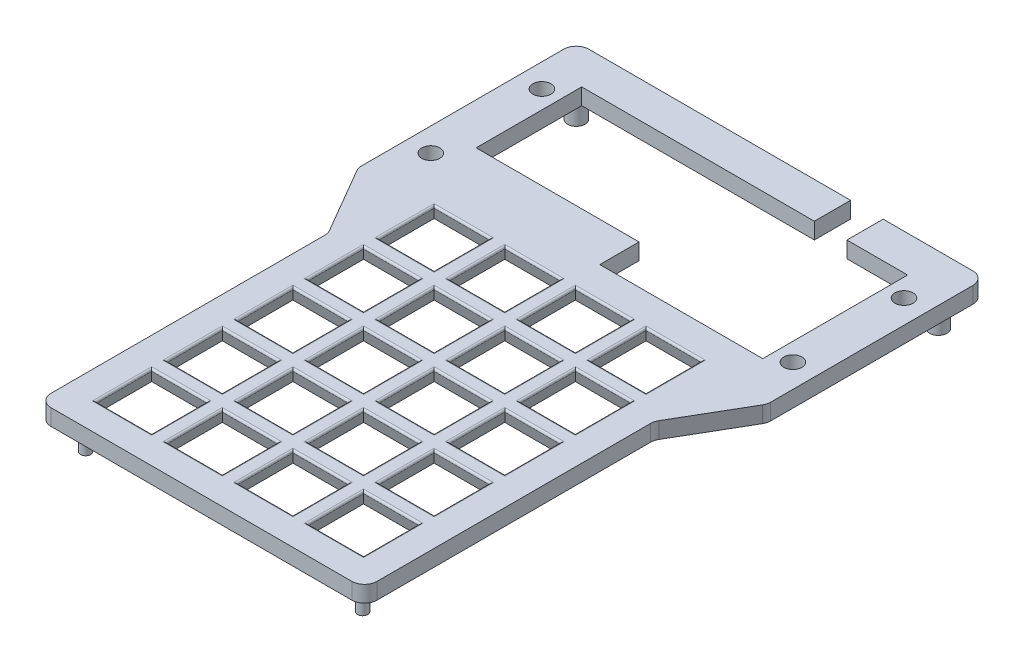
SolidWorks part; units mm, degrees
ref_plane "Front Plane" through (0, 0, 0) normal (0, 0, 1) x (1, 0, 0)
ref_plane "Top Plane" through (0, 0, 0) normal (0, 1, 0) x (1, 0, 0)
ref_plane "Right Plane" through (0, 0, 0) normal (1, 0, 0) x (0, 0, -1)
sketch "Sketch1" plane through (0, 0, 0) normal (0, 1, 0) x (1, 0, 0)
  line L0 (-57.5973, -8.4441) -> (-46.0973, -28.1941)
  line L1 (-46.0973, 51.8059) -> (43.9027, 51.8059)
  line L2 (-46.0973, 51.8059) -> (-46.0973, -108.1941)
  line L3 (-46.0973, -108.1941) -> (43.9027, -108.1941)
  line L4 (43.9027, 51.8059) -> (43.9027, -108.1941)
  line L5 (-57.5973, 51.8059) -> (55.4027, 51.8059)
  line L6 (-57.5973, 51.8059) -> (-57.5973, -8.4441)
  line L7 (-57.5973, -8.4441) -> (55.4027, -8.4441)
  line L8 (55.4027, 51.8059) -> (55.4027, -8.4441)
  line L9 (-57.5973, -8.4441) -> (-46.0973, -8.4441)
  line L10 (-46.0973, -8.4441) -> (-46.0973, -28.1941)
  line L11 (43.9027, -28.1941) -> (43.9027, -8.4441)
  line L12 (43.9027, -8.4441) -> (55.4027, -8.4441)
  line L13 (43.9027, -28.1941) -> (55.4027, -8.4441)
  point P12 (-1.0973, 51.8059)
  point P13 (-1.0973, 51.8059)
  dimension "D1" = 90
  dimension "D2" = 160
  dimension "D3" = 99.75
  dimension "D4" = 113
extrude "Boss-Extrude1" add sketch "Sketch1" along normal blind 4.5 contours L8 L5 L4 L7 | L2 L7 L4 L1 | L6 L7 L2 L5 | L7 L0 L2 | L7 L2 L3 L4 | L4 L13 L7
sketch "Sketch2" plane through (0, 0, 0) normal (0, -1, 0) x (1, 0, 0)
  line L0 (-46.0973, 108.1941) -> (43.9027, 108.1941) construction
  line L1 (43.9027, 28.1941) -> (43.9027, 108.1941) construction
  line L2 (-46.0973, 28.1941) -> (-46.0973, 108.1941) construction
  line L3 (-57.5973, -51.8059) -> (55.4027, -51.8059) construction
  line L4 (-57.5973, -51.8059) -> (-57.5973, 8.4441) construction
  line L5 (55.4027, -51.8059) -> (55.4027, 8.4441) construction
  circle A0 centre (-39.3473, 101.9441) radius 1.4
  circle A1 centre (37.1527, 101.9441) radius 1.4
  circle A2 centre (-51.0973, -45.3059) radius 2.4
  circle A3 centre (48.9027, -45.3059) radius 2.4
  circle A4 centre (-31.8473, -5.1309) radius 2.4
  circle A5 centre (-21.8473, -5.1309) radius 2.4
  point P12 (0, 0)
  point P19 (-39.6339, 101.6942)
  dimension "D5" = 4.8
  dimension "D6" = 4.8
  dimension "D12" = 4.8
  dimension "D13" = 4.8
  dimension "D16" = 2.8
  dimension "D17" = 2.8
  dimension "6.25" = 6.25
  dimension "D2" = 6.75
  dimension "D3" = 6.25
  dimension "D4" = 6.75
  dimension "D7" = 6.5
  dimension "D8" = 6.5
  dimension "D9" = 6.5
  dimension "D10" = 6.5
  dimension "D11" = 10
  dimension "D14" = 14.25
  dimension "D15" = 46.675
extrude "Boss-Extrude2" add sketch "Sketch2" along normal blind 7.5
sketch "Sketch3" plane through (0, 0, 0) normal (0, -1, 0) x (1, 0, 0)
  line L0 (-57.5973, -51.8059) -> (-57.5973, 8.4441) construction
  line L1 (-57.5973, -51.8059) -> (55.4027, -51.8059) construction
  line L2 (55.4027, -51.8059) -> (55.4027, 8.4441) construction
  line L8 (18.1527, -51.8059) -> (27.1527, -51.8059)
  line L9 (18.1527, -51.8059) -> (18.1527, -41.8059)
  line L10 (18.1527, -41.8059) -> (27.1527, -41.8059)
  line L11 (27.1527, -51.8059) -> (27.1527, -41.8059)
  line L12 (-46.0973, -12.6458) -> (43.9027, -12.6458)
  line L13 (-46.0973, -12.6458) -> (-46.0973, -41.8059)
  line L14 (-46.0973, -41.8059) -> (43.9027, -41.8059)
  line L15 (43.9027, -12.6458) -> (43.9027, -41.8059)
  line L16 (43.9027, -12.6458) -> (-1.0973, -12.6458)
  line L17 (43.9027, -12.6458) -> (43.9027, -1.8059)
  line L18 (43.9027, -1.8059) -> (-1.0973, -1.8059)
  line L19 (-1.0973, -12.6458) -> (-1.0973, -1.8059)
  circle A0 centre (-51.0973, -35.8059) radius 2.5
  circle A1 centre (48.9027, -35.8059) radius 2.5
  circle A2 centre (-51.0973, -5.1309) radius 2.5
  circle A3 centre (48.9027, -5.1309) radius 2.5
  circle A5 centre (-21.8473, -5.1309) radius 2.4
  circle A6 centre (-21.8473, -5.1309) radius 2.4
  point P28 (0, 0)
  point P29 (0, 0)
  point P30 (-1.0973, -51.8059)
  point P31 (-1.0973, -41.8059)
  point P32 (0, 0)
  point P34 (-1.0973, -6.0938)
  line M17 (-57.5973, -51.8059) -> (55.4027, -51.8059)
  dimension "D3" = 5
  dimension "D9" = 5
  dimension "D10" = 5
  dimension "D11" = 5
  dimension "D1" = 6.5
  dimension "D2" = 16
  dimension "D4" = 6.5
  dimension "D5" = 16
  dimension "D6" = 6.5
  dimension "D7" = 6.5
  dimension "D13" = 40
  dimension "D14" = 10
  dimension "D15" = 9
  dimension "D17" = 40
  dimension "D18" = 90
  dimension "D19" = 45
  dimension "D16" = 0
extrude "Cut-Extrude1" cut sketch "Sketch3" against normal blind 5 contours L15 L12 L13 L14 L10 | L19 L12 L17 L18 | L11 L10 L9 M17 | A1 | A0 | A2 | A3
sketch "Sketch4" plane through (0, 4.5, 0) normal (0, -1, 0) x (1, 0, 0)
  line L0 (-46.0973, 108.1941) -> (43.9027, 108.1941) construction
  line L1 (-37.8473, 100.1941) -> (-22.8473, 100.1941)
  line L2 (-37.8473, 100.1941) -> (-37.8473, 85.1941)
  line L3 (-37.8473, 85.1941) -> (-22.8473, 85.1941)
  line L4 (-22.8473, 100.1941) -> (-22.8473, 85.1941)
  line L5 (-46.0973, 28.1941) -> (-46.0973, 108.1941) construction
  line L6 (-18.3473, 85.1941) -> (-3.3473, 85.1941)
  line L7 (-18.3473, 85.1941) -> (-18.3473, 100.1941)
  line L8 (-18.3473, 100.1941) -> (-3.3473, 100.1941)
  line L9 (-3.3473, 85.1941) -> (-3.3473, 100.1941)
  line L10 (1.1527, 100.1941) -> (16.1527, 100.1941)
  line L11 (1.1527, 100.1941) -> (1.1527, 85.1941)
  line L12 (1.1527, 85.1941) -> (16.1527, 85.1941)
  line L13 (16.1527, 100.1941) -> (16.1527, 85.1941)
  line L14 (20.6527, 100.1941) -> (35.6527, 100.1941)
  line L15 (20.6527, 100.1941) -> (20.6527, 85.1941)
  line L16 (20.6527, 85.1941) -> (35.6527, 85.1941)
  line L17 (35.6527, 100.1941) -> (35.6527, 85.1941)
  line L19 (-18.3473, 41.6941) -> (-3.3473, 41.6941)
  line L20 (-18.3473, 41.6941) -> (-18.3473, 26.6941)
  line L21 (-37.8473, 80.6941) -> (-22.8473, 80.6941)
  line L22 (-37.8473, 80.6941) -> (-37.8473, 65.6941)
  line L23 (-37.8473, 65.6941) -> (-22.8473, 65.6941)
  line L24 (-22.8473, 80.6941) -> (-22.8473, 65.6941)
  line L25 (-18.3473, 80.6941) -> (-3.3473, 80.6941)
  line L26 (-18.3473, 80.6941) -> (-18.3473, 65.6941)
  line L27 (-18.3473, 65.6941) -> (-3.3473, 65.6941)
  line L28 (-3.3473, 80.6941) -> (-3.3473, 65.6941)
  line L29 (1.1527, 80.6941) -> (16.1527, 80.6941)
  line L30 (1.1527, 80.6941) -> (1.1527, 65.6941)
  line L31 (1.1527, 65.6941) -> (16.1527, 65.6941)
  line L32 (16.1527, 80.6941) -> (16.1527, 65.6941)
  line L33 (20.6527, 80.6941) -> (35.6527, 80.6941)
  line L34 (20.6527, 80.6941) -> (20.6527, 65.6941)
  line L35 (20.6527, 65.6941) -> (35.6527, 65.6941)
  line L36 (35.6527, 80.6941) -> (35.6527, 65.6941)
  line L37 (-37.8473, 61.1941) -> (-22.8473, 61.1941)
  line L38 (-37.8473, 61.1941) -> (-37.8473, 46.1941)
  line L39 (-37.8473, 46.1941) -> (-22.8473, 46.1941)
  line L40 (-22.8473, 61.1941) -> (-22.8473, 46.1941)
  line L41 (-18.3473, 61.1941) -> (-3.3473, 61.1941)
  line L42 (-18.3473, 61.1941) -> (-18.3473, 46.1941)
  line L43 (-18.3473, 46.1941) -> (-3.3473, 46.1941)
  line L44 (-3.3473, 61.1941) -> (-3.3473, 46.1941)
  line L45 (1.1527, 61.1941) -> (16.1527, 61.1941)
  line L46 (1.1527, 61.1941) -> (1.1527, 46.1941)
  line L47 (1.1527, 46.1941) -> (16.1527, 46.1941)
  line L48 (16.1527, 61.1941) -> (16.1527, 46.1941)
  line L49 (20.6527, 61.1941) -> (35.6527, 61.1941)
  line L50 (20.6527, 61.1941) -> (20.6527, 46.1941)
  line L51 (20.6527, 46.1941) -> (35.6527, 46.1941)
  line L52 (35.6527, 61.1941) -> (35.6527, 46.1941)
  line L53 (-37.8473, 41.6941) -> (-22.8473, 41.6941)
  line L54 (-37.8473, 41.6941) -> (-37.8473, 26.6941)
  line L55 (-37.8473, 26.6941) -> (-22.8473, 26.6941)
  line L56 (-22.8473, 41.6941) -> (-22.8473, 26.6941)
  line L57 (-18.3473, 26.6941) -> (-3.3473, 26.6941)
  line L58 (-3.3473, 41.6941) -> (-3.3473, 26.6941)
  line L59 (1.1527, 41.6941) -> (16.1527, 41.6941)
  line L60 (1.1527, 41.6941) -> (1.1527, 26.6941)
  line L61 (1.1527, 26.6941) -> (16.1527, 26.6941)
  line L62 (16.1527, 41.6941) -> (16.1527, 26.6941)
  line L63 (20.6527, 41.6941) -> (35.6527, 41.6941)
  line L64 (20.6527, 41.6941) -> (20.6527, 26.6941)
  line L65 (20.6527, 26.6941) -> (35.6527, 26.6941)
  line L66 (35.6527, 41.6941) -> (35.6527, 26.6941)
  line L67 (-37.8473, 22.1941) -> (-22.8473, 22.1941)
  line L68 (-37.8473, 22.1941) -> (-37.8473, 7.1941)
  line L69 (-37.8473, 7.1941) -> (-22.8473, 7.1941)
  line L70 (-22.8473, 22.1941) -> (-22.8473, 7.1941)
  line L71 (-18.3473, 22.1941) -> (-3.3473, 22.1941)
  line L72 (-18.3473, 22.1941) -> (-18.3473, 7.1941)
  line L73 (-18.3473, 7.1941) -> (-3.3473, 7.1941)
  line L74 (-3.3473, 22.1941) -> (-3.3473, 7.1941)
  line L75 (1.1527, 22.1941) -> (16.1527, 22.1941)
  line L76 (1.1527, 22.1941) -> (1.1527, 7.1941)
  line L77 (1.1527, 7.1941) -> (16.1527, 7.1941)
  line L78 (16.1527, 22.1941) -> (16.1527, 7.1941)
  line L79 (20.6527, 22.1941) -> (35.6527, 22.1941)
  line L80 (20.6527, 22.1941) -> (20.6527, 7.1941)
  line L81 (20.6527, 7.1941) -> (35.6527, 7.1941)
  line L82 (35.6527, 22.1941) -> (35.6527, 7.1941)
  dimension "D1" = 8
  dimension "D2" = 15
  dimension "D3" = 15
  dimension "D4" = 15
  dimension "D5" = 15
  dimension "D6" = 8
  dimension "D7" = 15
  dimension "D8" = 15
  dimension "D9" = 15
  dimension "D10" = 15
  dimension "D11" = 8
  dimension "D12" = 8
  dimension "D13" = 4.5
  dimension "D14" = 4.5
  dimension "D15" = 4.5
  dimension "D16" = 8.25
  dimension "D17" = 15
  dimension "D18" = 15
  dimension "D19" = 15
  dimension "D20" = 15
  dimension "D21" = 15
  dimension "D22" = 15
  dimension "D23" = 15
  dimension "D24" = 15
  dimension "D25" = 15
  dimension "D26" = 15
  dimension "D27" = 15
  dimension "D28" = 15
  dimension "D29" = 15
  dimension "D30" = 15
  dimension "D31" = 15
  dimension "D32" = 15
  dimension "D33" = 15
  dimension "D34" = 15
  dimension "D35" = 15
  dimension "D36" = 15
  dimension "D37" = 15
  dimension "D38" = 15
  dimension "D39" = 15
  dimension "D40" = 15
  dimension "D41" = 15
  dimension "D42" = 15
  dimension "D43" = 15
  dimension "D44" = 15
  dimension "D45" = 15
  dimension "D46" = 15
  dimension "D47" = 15
  dimension "D48" = 15
  dimension "D49" = 4.5
  dimension "D50" = 4.5
  dimension "D51" = 4.5
  dimension "D52" = 4.5
  dimension "D53" = 4.5
  dimension "D54" = 4.5
  dimension "D55" = 4.5
  dimension "D56" = 4.5
  dimension "D57" = 4.5
  dimension "D58" = 4.5
  dimension "D59" = 4.5
  dimension "D60" = 4.5
  dimension "D61" = 4.5
  dimension "D62" = 4.5
  dimension "D63" = 4.5
  dimension "D64" = 4.5
extrude "Cut-Extrude2" cut sketch "Sketch4" along normal up to surface (4.5 mm away) draft 20
fillet "Fillet1" radius 3.5 8 edges at (-57.5973, 2.25, 8.4441) (-46.0973, 2.25, 28.1941) (-46.0973, 2.25, 108.1941) (43.9027, 2.25, 108.1941) (43.9027, 2.25, 28.1941) (55.4027, 2.25, 8.4441) (55.4027, 2.25, -51.8059) (-57.5973, 2.25, -51.8059)
fillet "Fillet3" radius 0.5 80 edges at (-37.8473, 4.5, 92.6941) (-30.3473, 4.5, 100.1941) (-30.3473, 4.5, 85.1941) (-22.8473, 4.5, 92.6941) (-18.3473, 4.5, 92.6941) (-10.8473, 4.5, 100.1941) (-10.8473, 4.5, 85.1941) (-3.3473, 4.5, 92.6941) (8.6527, 4.5, 100.1941) (1.1527, 4.5, 92.6941) (8.6527, 4.5, 85.1941) (16.1527, 4.5, 92.6941) (28.1527, 4.5, 100.1941) (35.6527, 4.5, 92.6941) (28.1527, 4.5, 85.1941) (20.6527, 4.5, 92.6941) (28.1527, 4.5, 80.6941) (35.6527, 4.5, 73.1941) (28.1527, 4.5, 65.6941) (20.6527, 4.5, 73.1941) (8.6527, 4.5, 65.6941) (1.1527, 4.5, 73.1941) (8.6527, 4.5, 80.6941) (16.1527, 4.5, 73.1941) (-3.3473, 4.5, 73.1941) (-10.8473, 4.5, 65.6941) (-10.8473, 4.5, 80.6941) (-18.3473, 4.5, 73.1941) (-30.3473, 4.5, 65.6941) (-22.8473, 4.5, 73.1941) (-30.3473, 4.5, 80.6941) (-37.8473, 4.5, 73.1941) (-30.3473, 4.5, 61.1941) (-22.8473, 4.5, 53.6941) (-30.3473, 4.5, 46.1941) (-37.8473, 4.5, 53.6941) (-10.8473, 4.5, 46.1941) (-18.3473, 4.5, 53.6941) (-10.8473, 4.5, 61.1941) (-3.3473, 4.5, 53.6941) (8.6527, 4.5, 46.1941) (1.1527, 4.5, 53.6941) (8.6527, 4.5, 61.1941) (16.1527, 4.5, 53.6941) (28.1527, 4.5, 46.1941) (20.6527, 4.5, 53.6941) (28.1527, 4.5, 61.1941) (35.6527, 4.5, 53.6941) (28.1527, 4.5, 26.6941) (20.6527, 4.5, 34.1941) (28.1527, 4.5, 41.6941) (35.6527, 4.5, 34.1941) (8.6527, 4.5, 26.6941) (16.1527, 4.5, 34.1941) (8.6527, 4.5, 41.6941) (1.1527, 4.5, 34.1941) (-10.8473, 4.5, 26.6941) (-3.3473, 4.5, 34.1941) (-10.8473, 4.5, 41.6941) (-18.3473, 4.5, 34.1941) (-37.8473, 4.5, 34.1941) (-30.3473, 4.5, 41.6941) (-30.3473, 4.5, 26.6941) (-22.8473, 4.5, 34.1941) (-30.3473, 4.5, 7.1941) (-37.8473, 4.5, 14.6941) (-30.3473, 4.5, 22.1941) (-22.8473, 4.5, 14.6941) (-10.8473, 4.5, 7.1941) (-3.3473, 4.5, 14.6941) (-10.8473, 4.5, 22.1941) (-18.3473, 4.5, 14.6941) (1.1527, 4.5, 14.6941) (8.6527, 4.5, 22.1941) (8.6527, 4.5, 7.1941) (16.1527, 4.5, 14.6941) (20.6527, 4.5, 14.6941) (28.1527, 4.5, 7.1941) (28.1527, 4.5, 22.1941) (35.6527, 4.5, 14.6941)
